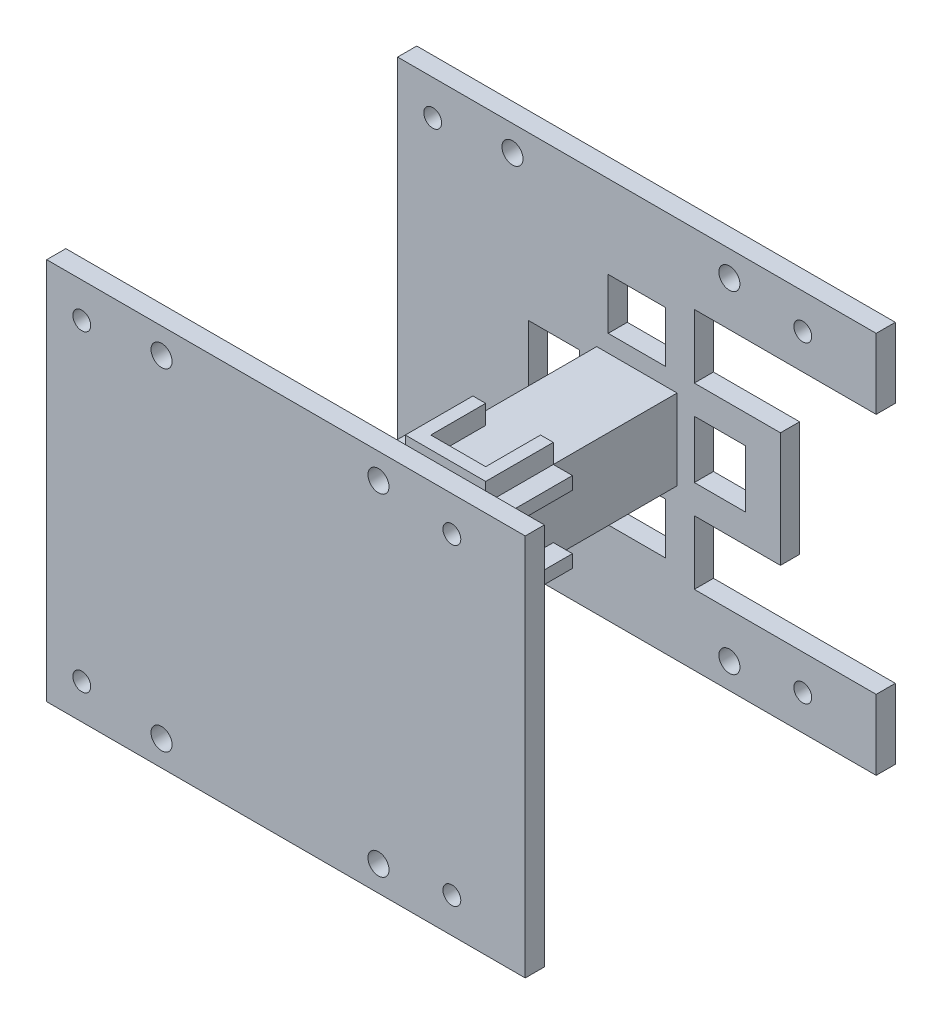
SolidWorks part; units mm, degrees
ref_plane "前视基准面" through (0, 0, 0) normal (0, 0, 1) x (1, 0, 0)
ref_plane "上视基准面" through (0, 0, 0) normal (0, 1, 0) x (1, 0, 0)
ref_plane "右视基准面" through (0, 0, 0) normal (1, 0, 0) x (0, 0, -1)
sketch "草图4" plane through (0, 0, 0) normal (0, 0, 1) x (1, 0, 0)
  line L0 (-55, 30) -> (20, -30) construction
  line L1 (-39, 30) -> (20, 30)
  line L3 (-39, -30) -> (20, -30)
  line L5 (20, 19) -> (5, 19)
  line L6 (5, 19) -> (5, -19)
  line L7 (20, 30) -> (-55, -30) construction
  line L13 (20, 30) -> (20, 19)
  line L24 (-39, 30) -> (-55, 30)
  line L27 (-55, -30) -> (-39, -30)
  line L35 (5, -19) -> (20, -19)
  line L36 (20, -19) -> (20, -30)
  line L37 (-55, 30) -> (-55, -30)
  circle A0 centre (-49.5, 24.5) radius 1.4
  circle A1 centre (8.5, 24.5) radius 1.4
  circle A2 centre (-3, 26) radius 1.65
  circle A3 centre (-37, 26) radius 1.65
  circle A4 centre (-37, -26) radius 1.65
  circle A5 centre (-3, -26) radius 1.65
  circle A6 centre (8.5, -24.5) radius 1.4
  circle A7 centre (-49.5, -24.5) radius 1.4
  circle A8 centre (8.5, 24.5) radius 2.5 construction
  circle A9 centre (-3, 26) radius 2.5 construction
  point P0 (0, 0)
  dimension "D3" = 2.8
  dimension "D4" = 2.8
  dimension "D9" = 3.3
  dimension "D10" = 3.3
  dimension "D15" = 5
  dimension "D16" = 5
  dimension "D1" = 75
  dimension "D2" = 60
  dimension "D5" = 11
  dimension "D6" = 58
  dimension "D7" = 5.5
  dimension "D8" = 5.5
  dimension "D11" = 11
  dimension "D12" = 15
  dimension "D13" = 34
extrude "凸台-拉伸1" add sketch "草图4" along normal blind 3
sketch "草图5" plane through (0, 0, 3) normal (0, 0, 1) x (1, 0, 0)
  line L0 (-55, 30) -> (20, -30) construction
  line L1 (20, 30) -> (-55, -30) construction
  line L3 (-23.8, 6.3) -> (-11.2, 6.3)
  line L4 (20, 19) -> (20, 30)
  line L5 (20, 30) -> (-55, 30)
  line L6 (-55, 30) -> (-55, -30)
  line L7 (-55, -30) -> (20, -30)
  line L8 (20, 19) -> (20, 30)
  line L9 (20, 30) -> (-55, 30)
  line L10 (-55, 30) -> (-55, -30)
  line L11 (-55, -30) -> (20, -30)
  line L12 (-23.8, 6.3) -> (-23.8, -6.3)
  line L13 (-23.8, -6.3) -> (-11.2, -6.3)
  line L14 (-11.2, 6.3) -> (-11.2, -6.3)
  line L15 (-23.8, 6.3) -> (-11.2, -6.3) construction
  line L16 (-23.8, -6.3) -> (-11.2, 6.3) construction
  line L19 (-11.2, 6.3) -> (-9.625, 6.3)
  line L21 (-9.625, -6.3) -> (-11.2, -6.3)
  line L25 (-23.8, -6.3) -> (-25.375, -6.3)
  line L27 (-25.375, 6.3) -> (-23.8, 6.3)
  line L28 (20, -30) -> (20, -19)
  line L29 (20, -30) -> (20, -19)
  line L30 (20, -19) -> (5, -19)
  line L31 (20, -19) -> (5, -19)
  line L32 (5, -19) -> (5, 19)
  line L33 (5, -19) -> (5, 19)
  line L34 (5, 19) -> (20, 19)
  line L35 (5, 19) -> (20, 19)
  point P2 (-17.5, 0)
  dimension "D2" = 12.6
  dimension "D3" = 12.6
  dimension "D1" = 0
extrude "凸台-拉伸2" add sketch "草图5" along normal blind 30 contours L14 L3 L12 L13
sketch "草图6" plane through (0, 0, 0) normal (0, 0, -1) x (-1, 0, 0)
  line L2 (13, 9) -> (13, 17)
  line L9 (13, 17) -> (22, 17)
  line L10 (22, 17) -> (22, 9)
  line L12 (34.5, 4.5) -> (34.5, -4.5)
  line L13 (34.5, -4.5) -> (26.5, -4.5)
  line L14 (22, -9) -> (22, -17)
  line L15 (22, -17) -> (13, -17)
  line L16 (13, -17) -> (13, -9)
  line L18 (0.5, -4.5) -> (0.5, 4.5)
  line L19 (0.5, 4.5) -> (8.5, 4.5)
  line L22 (13, 9) -> (22, 9)
  line L25 (26.5, 4.5) -> (26.5, -4.5)
  line L26 (13, -9) -> (22, -9)
  line L27 (8.5, -4.5) -> (8.5, 4.5)
  line L28 (8.5, -4.5) -> (0.5, -4.5)
  line L29 (26.5, 4.5) -> (34.5, 4.5)
  point P6 (17.5, 0)
  dimension "D14" = 8
  dimension "D15" = 8
  dimension "D16" = 8
  dimension "D17" = 8
extrude "切除-拉伸2" cut sketch "草图6" against normal through all
sketch "草图8" plane through (-11.2, 0, 0) normal (1, 0, 0) x (0, 0, -1)
  line L0 (-31, 4.3) -> (-22.4, 4.3)
  line L1 (-31, 4.3) -> (-31, -4.3)
  line L2 (-31, -4.3) -> (-22.4, -4.3)
  line L3 (-22.4, -4.3) -> (-22.4, -6.3)
  line L4 (-3, -6.3) -> (-3, 6.3)
  line L5 (-3, 6.3) -> (-33, 6.3)
  line L6 (-33, 6.3) -> (-33, -6.3)
  line L7 (-33, -6.3) -> (-3, -6.3)
  line L9 (-22.4, 6.3) -> (-33, 6.3)
  line L10 (-33, 6.3) -> (-33, -6.3)
  line L11 (-33, -6.3) -> (-22.4, -6.3)
  line L12 (-33, 0) -> (-20.4591, 0) construction
  line L13 (-22.4, 4.3) -> (-22.4, 6.3)
  point P10 (-31, 0)
  dimension "D2" = 2
  dimension "D3" = 2
  dimension "D4" = 8.6
  dimension "D1" = 0
extrude "凸台-拉伸3" add sketch "草图8" along normal blind 3
sketch "草图10" plane through (-23.8, 0, 0) normal (-1, 0, 0) x (0, 0, 1)
  line L0 (33, 0) -> (22.2066, 0) construction
  line L1 (22.4, 6.3) -> (22.4, 4.3)
  line L2 (22.4, 4.3) -> (31, 4.3)
  line L3 (31, 4.3) -> (31, -4.3)
  line L4 (3, 6.3) -> (3, -6.3)
  line L5 (3, -6.3) -> (33, -6.3)
  line L7 (33, 6.3) -> (3, 6.3)
  line L11 (33, 6.3) -> (22.4, 6.3)
  line L12 (22.4, -4.3) -> (31, -4.3)
  line L13 (22.4, -6.3) -> (22.4, -4.3)
  line L18 (22.4, -6.3) -> (33, -6.3)
  line L20 (33, -6.3) -> (33, 6.3)
  line L21 (33, -6.3) -> (33, 6.3)
  point P12 (31, 0)
  dimension "D2" = 2
  dimension "D4" = 8.6
  dimension "D1" = 0
extrude "凸台-拉伸4" add sketch "草图10" along normal blind 3
sketch "草图11" plane through (0, -6.3, 0) normal (0, -1, 0) x (1, 0, 0)
  line L0 (-23.8, 22.4) -> (-23.8, 33)
  line L1 (-11.2, 22.4) -> (-11.2, 33)
  line L2 (-17.5, 33.5045) -> (-17.5, 25.0515) construction
  line L3 (-23.8, 22.4) -> (-21.8, 22.4)
  line L4 (-21.8, 22.4) -> (-21.8, 31)
  line L5 (-21.8, 31) -> (-13.2, 31)
  line L6 (-13.2, 22.4) -> (-13.2, 31)
  line L7 (-11.2, 22.4) -> (-13.2, 22.4)
  line L8 (-23.8, 3) -> (-11.2, 3)
  line L9 (-11.2, 3) -> (-11.2, 22.4)
  line L10 (-11.2, 22.4) -> (-8.2, 22.4)
  line L11 (-8.2, 22.4) -> (-8.2, 33)
  line L12 (-8.2, 33) -> (-26.8, 33)
  line L15 (-23.8, 22.4) -> (-23.8, 3)
  line L20 (-11.2, 33) -> (-23.8, 33)
  line L24 (-26.8, 22.4) -> (-23.8, 22.4) construction
  line L31 (-26.8, 33) -> (-26.8, 22.4)
  line L32 (-26.8, 22.4) -> (-23.8, 22.4)
  point P17 (-17.5, 31)
  point P19 (-22.8, 22.4)
  dimension "D2" = 2
  dimension "D3" = 2
  dimension "D1" = 0
extrude "凸台-拉伸5" add sketch "草图11" along normal blind 3
sketch "草图12" plane through (0, 6.3, 0) normal (0, 1, 0) x (1, 0, 0)
  line L0 (-23.8, -22.4) -> (-23.8, -33)
  line L1 (-11.2, -22.4) -> (-11.2, -33)
  line L2 (-23.8, -22.4) -> (-21.8, -22.4)
  line L3 (-21.8, -22.4) -> (-21.8, -31)
  line L4 (-17.5, -33) -> (-17.5, -24.9016) construction
  line L5 (-21.8, -31) -> (-13.2, -31)
  line L6 (-13.2, -22.4) -> (-13.2, -31)
  line L7 (-11.2, -22.4) -> (-13.2, -22.4)
  line L8 (-11.2, -3) -> (-23.8, -3)
  line L9 (-23.8, -3) -> (-23.8, -22.4)
  line L12 (-26.8, -33) -> (-8.2, -33)
  line L13 (-8.2, -33) -> (-8.2, -22.4)
  line L14 (-8.2, -22.4) -> (-11.2, -22.4)
  line L15 (-11.2, -22.4) -> (-11.2, -3)
  line L20 (-23.8, -33) -> (-11.2, -33)
  line L30 (-23.8, -22.4) -> (-26.8, -22.4)
  line L31 (-26.8, -22.4) -> (-26.8, -33)
  point P17 (-17.5, -31)
  dimension "D2" = 2
  dimension "D3" = 2
  dimension "D1" = 0
extrude "凸台-拉伸6" add sketch "草图12" along normal blind 3
sketch "草图13" plane through (0, 0, 33) normal (0, 0, 1) x (1, 0, 0)
  line L0 (-23.8, 5.04) -> (-11.2, -5.04) construction
  line L1 (-11.2, 5.04) -> (-23.8, -5.04) construction
  line L3 (-23.8, 6.3) -> (-11.2, 6.3)
  line L12 (-23.8, 6.3) -> (-23.8, -6.3)
  line L13 (-23.8, -6.3) -> (-11.2, -6.3)
  line L14 (-11.2, 6.3) -> (-11.2, -6.3)
  line L15 (-23.8, 6.3) -> (-11.2, -6.3) construction
  line L16 (-23.8, -6.3) -> (-11.2, 6.3) construction
  point P2 (-17.5, 0)
  dimension "D2" = 12.6
  dimension "D3" = 12.6
extrude "凸台-拉伸7" add sketch "草图13" along normal blind 22
sketch "草图14" plane through (0, 0, 55) normal (0, 0, 1) x (1, 0, 0)
  line L0 (-55, 30) -> (20, -30) construction
  line L1 (-39, 30) -> (20, 30)
  line L3 (-39, -30) -> (20, -30)
  line L5 (-55, 30) -> (-48.1001, 24.4801) construction
  line L6 (-55, -30) -> (-48.1001, -24.4801) construction
  line L7 (20, 30) -> (-55, -30) construction
  line L13 (20, 30) -> (20, -30)
  line L24 (-39, 30) -> (-55, 30)
  line L27 (-55, -30) -> (-39, -30)
  line L37 (-55, 30) -> (-55, -30)
  circle A0 centre (-49.5, 24.5) radius 1.4
  circle A1 centre (8.5, 24.5) radius 1.4
  circle A2 centre (-3, 26) radius 1.65
  circle A3 centre (-37, 26) radius 1.65
  circle A4 centre (-37, -26) radius 1.65
  circle A5 centre (-3, -26) radius 1.65
  circle A6 centre (8.5, -24.5) radius 1.4
  circle A7 centre (-49.5, -24.5) radius 1.4
  circle A8 centre (8.5, 24.5) radius 2.5 construction
  circle A9 centre (-3, 26) radius 2.5 construction
  point P0 (0, 0)
  dimension "D3" = 2.8
  dimension "D4" = 2.8
  dimension "D9" = 3.3
  dimension "D10" = 3.3
  dimension "D15" = 5
  dimension "D16" = 5
  dimension "D1" = 75
  dimension "D2" = 60
  dimension "D6" = 58
  dimension "D7" = 5.5
  dimension "D8" = 5.5
  dimension "D13" = 34
extrude "凸台-拉伸8" add sketch "草图14" along normal blind 3
sketch "草图15" plane through (0, 0, 3) normal (0, 0, 1) x (1, 0, 0)
  line L0 (5, 19) -> (-8.5, 19)
  line L1 (-8.5, 19) -> (-8.5, 9)
  line L2 (-8.5, 9) -> (5, 9)
  line L3 (5, -9) -> (-8.5, -9)
  line L4 (5, 9) -> (5, 19)
  line L8 (20, -30) -> (20, -19)
  line L9 (20, -19) -> (5, -19)
  line L10 (5, -19) -> (5, 19)
  line L11 (5, 19) -> (20, 19)
  line L12 (20, 19) -> (20, 30)
  line L13 (20, 30) -> (-55, 30)
  line L14 (-55, 30) -> (-55, -30)
  line L15 (-55, -30) -> (20, -30)
  line L16 (20, -30) -> (20, -19)
  line L18 (5, -19) -> (5, -9)
  line L20 (20, 19) -> (20, 30)
  line L21 (20, 30) -> (-55, 30)
  line L22 (-55, 30) -> (-55, -30)
  line L23 (-55, -30) -> (20, -30)
  line L52 (-8.5, -9) -> (-8.5, -19)
  line L53 (-8.5, -19) -> (5, -19)
  line M51 (5, -19) -> (5, 19)
  dimension "D1" = 0
extrude "切除-拉伸3" cut sketch "草图15" against normal through all contours L1 L2 L0 M51 | L52 L53 L3 M51
